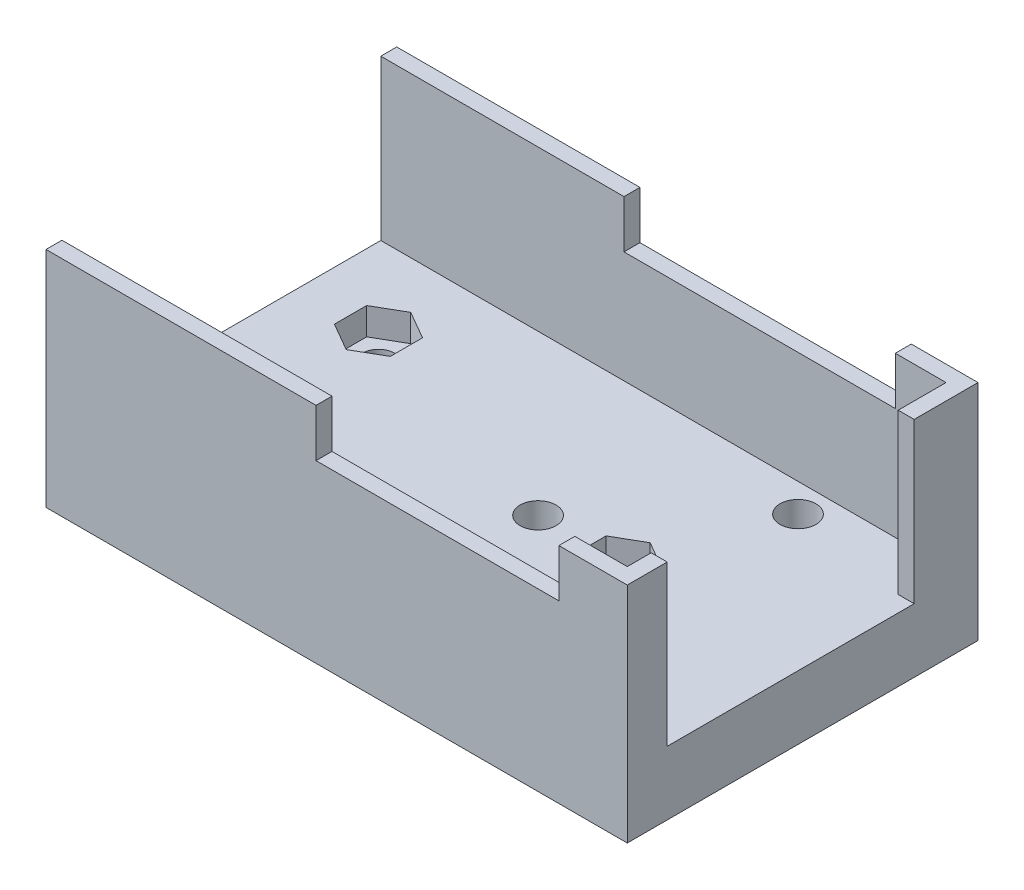
SolidWorks part; units mm, degrees
ref_plane "Front Plane" through (0, 0, 0) normal (0, 0, 1) x (1, 0, 0)
ref_plane "Top Plane" through (0, 0, 0) normal (0, 1, 0) x (1, 0, 0)
ref_plane "Right Plane" through (0, 0, 0) normal (1, 0, 0) x (0, 0, -1)
sketch "Sketch1" plane through (0, 0, 0) normal (0, 1, 0) x (1, 0, 0)
  line L0 (0, 2.5) -> (0, -2.5) construction
  line L1 (-33.5, 19.475) -> (33.5, 19.475) construction
  line L2 (-33.5, 19.475) -> (-33.5, -19.475) construction
  line L3 (-33.5, -19.475) -> (33.5, -19.475) construction
  line L4 (33.5, 19.475) -> (33.5, -19.475) construction
  line L5 (-2.5, 0) -> (2.5, 0) construction
  line L6 (-12.5, 19.475) -> (-12.5, -19.475) construction
  line L7 (30.5, 14.5022) -> (30.5, 19.3378) construction
  line L8 (23.7367, 16.92) -> (37.2633, 16.92) construction
  line L9 (30.5, -14.5022) -> (30.5, -19.3378) construction
  line L10 (23.7367, -16.92) -> (37.2633, -16.92) construction
  line L11 (30.5, 15.49) -> (29.1342, 15.49) construction
  line L12 (29.2815, -18.37) -> (31.7185, -18.37) construction
  line L13 (29.05, 15.9788) -> (29.05, 17.8612) construction
  line L14 (-10.95, -19.6462) -> (-10.95, -14.1938) construction
  line L15 (30.5, 15.47) -> (32.3745, 15.47) construction
  line L16 (30.5, -15.47) -> (32.3745, -15.47) construction
  line L17 (30.5, 15.47) -> (26.9196, 15.47) construction
  line L18 (30.5, 18.37) -> (26.9852, 18.37) construction
  line L19 (-12.5, 26.9594) -> (33.5, 26.9594) construction
  line L20 (10.5, 26.9594) -> (10.5, 19.475) construction
  line L21 (-9.5, 18.37) -> (-5.9852, 18.37) construction
  line L22 (-9.5, 15.47) -> (-5.9196, 15.47) construction
  line L23 (-9.5, -15.47) -> (-11.3745, -15.47) construction
  line L24 (-9.5, 15.47) -> (-11.3745, 15.47) construction
  line L25 (31.95, -19.2534) -> (31.95, -14.5866) construction
  line L26 (-8.7825, 18.36) -> (-7.3409, 18.36) construction
  line L28 (-9.5, 15.49) -> (-8.1342, 15.49) construction
  line L29 (-2.7367, -16.92) -> (-16.2633, -16.92) construction
  line L30 (-9.5, -14.5022) -> (-9.5, -19.3378) construction
  line L31 (-2.7367, 16.92) -> (-16.2633, 16.92) construction
  line L32 (-9.5, 14.5022) -> (-9.5, 19.3378) construction
  line L33 (-8.05, 16.2789) -> (-8.05, 17.5611) construction
  line L34 (-10.95, 15.8763) -> (-10.95, 17.9637) construction
  line L35 (31.95, 15.697) -> (31.95, 18.143) construction
  circle A4 centre (30.5, 16.92) radius 1.45 construction
  circle A5 centre (30.5, -16.92) radius 1.45 construction
  circle A6 centre (-9.5, -16.92) radius 1.45 construction
  circle A7 centre (-9.5, 16.92) radius 1.45 construction
  point P4 (0, 19.475)
  point P11 (0, 0)
  point P15 (0, 0)
  point P16 (-33.5, 0)
  point P22 (30.5, 16.92)
  point P24 (30.5, 16.92)
  point P32 (30.5, -18.37)
  point P35 (29.05, 16.92)
  point P56 (-10.95, -16.92)
  point P66 (31.95, -16.92)
  point P82 (-9.5, 16.92)
  point P83 (-9.5, 16.92)
  point P87 (-8.05, 16.92)
  point P89 (-10.95, 16.92)
  point P92 (31.95, 16.92)
  dimension "D7" = 30.94
  dimension "D9" = 42.9
  dimension "D1" = 5
  dimension "D2" = 5
  dimension "D3" = 38.95
  dimension "D4" = 67
  dimension "D5" = 46
  dimension "D6" = 21
  dimension "D8" = 36.74
  dimension "D10" = 1.105
  dimension "D11" = 0.02
  dimension "D12" = 0.02
  dimension "D13" = 0
  dimension "D14" = 1.55
  dimension "D15" = 37.1
  dimension "D16" = 42.9
sketch "Sketch2" plane through (0, 0, 0) normal (0, 1, 0) x (1, 0, 0)
  line L0 (-12.5, 19.475) -> (-12.5, -19.475) construction
  line L1 (-33.5, 19.475) -> (33.5, 19.475) construction
  line L2 (-33.5, 19.475) -> (-33.5, -19.475) construction
  line L3 (-33.5, -19.475) -> (33.5, -19.475) construction
  line L4 (33.5, 19.475) -> (33.5, -19.475) construction
  line L5 (17, 18.42) -> (21, 18.42) construction
  line L6 (-3, -14.475) -> (27.43, -14.475) construction
  line L7 (-3, -14.475) -> (-3, -19.475) construction
  line L9 (27.43, -14.475) -> (27.43, -19.475) construction
  line L11 (27.64, 19.475) -> (27.64, 14.475) construction
  line L12 (27.64, 14.475) -> (-6.36, 14.475) construction
  line L13 (-6.36, 19.475) -> (-6.36, 14.475) construction
  line L14 (0.85, 2) -> (4.85, 2) construction
  line L15 (0.85, 2) -> (0.85, -2) construction
  line L16 (0.85, -2) -> (4.85, -2) construction
  line L17 (4.85, 2) -> (4.85, -2) construction
  line L18 (17, 18.42) -> (17, 14.42) construction
  line L19 (17, 14.42) -> (21, 14.42) construction
  line L20 (21, 18.42) -> (21, 14.42) construction
  line L21 (17, -14.42) -> (21, -14.42) construction
  line L22 (17, -14.42) -> (17, -18.42) construction
  line L23 (17, -18.42) -> (21, -18.42) construction
  line L24 (21, -14.42) -> (21, -18.42) construction
  line L25 (19, 16.42) -> (19, -16.42) construction
  line L26 (19, 0) -> (11.327, 0) construction
  line L27 (30.5, -16.92) -> (24.299, -16.92) construction
  line L28 (29.05, -18.37) -> (31.95, -18.37)
  line L29 (29.05, -18.37) -> (29.05, -15.47)
  line L30 (29.05, -15.47) -> (31.95, -15.47)
  line L31 (31.95, -18.37) -> (31.95, -15.47)
  line L32 (29.05, -18.37) -> (31.95, -15.47) construction
  line L33 (29.05, -15.47) -> (31.95, -18.37) construction
  line L35 (-10.95, 15.47) -> (-8.05, 15.47)
  line L36 (-10.95, 15.47) -> (-10.95, 18.37)
  line L37 (-10.95, 18.37) -> (-8.05, 18.37)
  line L38 (-8.05, 15.47) -> (-8.05, 18.37)
  line L39 (-10.95, 15.47) -> (-8.05, 18.37) construction
  line L40 (-10.95, 18.37) -> (-8.05, 15.47) construction
  circle A0 centre (-9.5, 16.92) radius 1.45 construction
  circle A1 centre (30.5, 16.92) radius 1.45 construction
  circle A2 centre (30.5, -16.92) radius 1.45 construction
  circle A3 centre (-9.5, -16.92) radius 1.45 construction
  circle A4 centre (2.85, 0) radius 2 construction
  circle A7 centre (19, 16.42) radius 2 construction
  circle A8 centre (19, -16.42) radius 2 construction
  dimension "D8" = 4
  dimension "D9" = 4
  dimension "D10" = 4
  dimension "D1" = 9.5
  dimension "D2" = 30.43
  dimension "D3" = 6.07
  dimension "D4" = 5
  dimension "D5" = 34
  dimension "D6" = 5
  dimension "D7" = 6.14
  dimension "D11" = 36.84
  dimension "D12" = 20.15
  dimension "D13" = 14.95
  dimension "D14" = 31.95
  dimension "D15" = 42.9
  dimension "D16" = 36.84
sketch "Sketch3" plane through (0, 0, 0) normal (0, 1, 0) x (1, 0, 0)
  line L0 (-12.5, 19.975) -> (34, 19.975) construction
  line L1 (34, 19.975) -> (34, -19.975) construction
  line L2 (34, -19.975) -> (-12.5, -19.975) construction
  line L3 (-12.5, 19.975) -> (-36.8371, 19.975) construction
  line L4 (-12.5, -19.975) -> (-36.8371, -19.975) construction
  line L5 (-29.1596, 2.0082) -> (-25.1596, 2.0082) construction
  line L6 (33.5, 19.475) -> (33.5, -19.475) construction
  line L7 (-33.5, -19.475) -> (33.5, -19.475) construction
  line L8 (-36.8371, 19.975) -> (-36.8371, 21.975) construction
  line L9 (-36.8371, 21.975) -> (36, 21.975) construction
  line L11 (36, -21.975) -> (-36.8371, -21.975) construction
  line L12 (-36.8371, -21.975) -> (-36.8371, -19.975) construction
  line L13 (-29.1596, 12.0082) -> (-25.1596, 12.0082) construction
  line L14 (-29.1596, 12.0082) -> (-29.1596, 8.0082) construction
  line L15 (-29.1596, 8.0082) -> (-25.1596, 8.0082) construction
  line L16 (-25.1596, 12.0082) -> (-25.1596, 8.0082) construction
  line L17 (10.8404, 12.0082) -> (14.8404, 12.0082) construction
  line L18 (10.8404, 12.0082) -> (10.8404, 8.0082) construction
  line L19 (10.8404, 8.0082) -> (14.8404, 8.0082) construction
  line L20 (14.8404, 12.0082) -> (14.8404, 8.0082) construction
  line L21 (-29.1596, 2.0082) -> (-29.1596, -1.9918) construction
  line L22 (-29.1596, -1.9918) -> (-25.1596, -1.9918) construction
  line L23 (-25.1596, 2.0082) -> (-25.1596, -1.9918) construction
  line L24 (10.8404, 2.0082) -> (14.8404, 2.0082) construction
  line L25 (10.8404, 2.0082) -> (10.8404, -1.9918) construction
  line L26 (10.8404, -1.9918) -> (14.8404, -1.9918) construction
  line L27 (14.8404, 2.0082) -> (14.8404, -1.9918) construction
  line L28 (-19.1596, 2.0082) -> (-15.1596, 2.0082) construction
  line L29 (36, 21.975) -> (36, 13.975) construction
  line L30 (36, -21.975) -> (36, -16.975) construction
  line L31 (-19.1596, 12.0082) -> (-15.1596, 12.0082) construction
  line L32 (-19.1596, 12.0082) -> (-19.1596, 8.0082) construction
  line L33 (-19.1596, 8.0082) -> (-15.1596, 8.0082) construction
  line L34 (-15.1596, 12.0082) -> (-15.1596, 8.0082) construction
  line L35 (-9.1596, 12.0082) -> (-5.1596, 12.0082) construction
  line L36 (-9.1596, 12.0082) -> (-9.1596, 8.0082) construction
  line L37 (-9.1596, 8.0082) -> (-5.1596, 8.0082) construction
  line L38 (-5.1596, 12.0082) -> (-5.1596, 8.0082) construction
  line L39 (0.8404, 12.0082) -> (4.8404, 12.0082) construction
  line L40 (0.8404, 12.0082) -> (0.8404, 8.0082) construction
  line L41 (0.8404, 8.0082) -> (4.8404, 8.0082) construction
  line L42 (4.8404, 12.0082) -> (4.8404, 8.0082) construction
  line L43 (-19.1596, 2.0082) -> (-19.1596, -1.9918) construction
  line L44 (-19.1596, -1.9918) -> (-15.1596, -1.9918) construction
  line L45 (-15.1596, 2.0082) -> (-15.1596, -1.9918) construction
  line L46 (-9.1596, 2.0082) -> (-5.1596, 2.0082) construction
  line L47 (-9.1596, 2.0082) -> (-9.1596, -1.9918) construction
  line L48 (-9.1596, -1.9918) -> (-5.1596, -1.9918) construction
  line L49 (-5.1596, 2.0082) -> (-5.1596, -1.9918) construction
  line L50 (0.8404, 2.0082) -> (4.8404, 2.0082) construction
  line L51 (0.8404, 2.0082) -> (0.8404, -1.9918) construction
  line L52 (0.8404, -1.9918) -> (4.8404, -1.9918) construction
  line L53 (4.8404, 2.0082) -> (4.8404, -1.9918) construction
  line L54 (-29.1596, -7.9918) -> (-25.1596, -7.9918) construction
  line L55 (-29.1596, -7.9918) -> (-29.1596, -11.9918) construction
  line L56 (-29.1596, -11.9918) -> (-25.1596, -11.9918) construction
  line L57 (-25.1596, -7.9918) -> (-25.1596, -11.9918) construction
  line L58 (10.8404, -7.9918) -> (14.8404, -7.9918) construction
  line L59 (10.8404, -7.9918) -> (10.8404, -11.9918) construction
  line L60 (10.8404, -11.9918) -> (14.8404, -11.9918) construction
  line L61 (14.8404, -7.9918) -> (14.8404, -11.9918) construction
  line L62 (-19.1596, -7.9918) -> (-15.1596, -7.9918) construction
  line L63 (-19.1596, -7.9918) -> (-19.1596, -11.9918) construction
  line L64 (-19.1596, -11.9918) -> (-15.1596, -11.9918) construction
  line L65 (-15.1596, -7.9918) -> (-15.1596, -11.9918) construction
  line L66 (-9.1596, -7.9918) -> (-5.1596, -7.9918) construction
  line L67 (-9.1596, -7.9918) -> (-9.1596, -11.9918) construction
  line L68 (-9.1596, -11.9918) -> (-5.1596, -11.9918) construction
  line L69 (-5.1596, -7.9918) -> (-5.1596, -11.9918) construction
  line L70 (0.8404, -7.9918) -> (4.8404, -7.9918) construction
  line L71 (0.8404, -7.9918) -> (0.8404, -11.9918) construction
  line L72 (0.8404, -11.9918) -> (4.8404, -11.9918) construction
  line L73 (4.8404, -7.9918) -> (4.8404, -11.9918) construction
  circle A0 centre (-27.1596, 10.0082) radius 2 construction
  circle A1 centre (12.8404, 10.0082) radius 2 construction
  circle A4 centre (-17.1596, 10.0082) radius 2 construction
  circle A5 centre (-7.1596, 10.0082) radius 2 construction
  circle A6 centre (2.8404, 10.0082) radius 2 construction
  circle A7 centre (-27.1596, 0.0082) radius 2 construction
  circle A8 centre (12.8404, 0.0082) radius 2 construction
  circle A9 centre (-17.1596, 0.0082) radius 2 construction
  circle A10 centre (-7.1596, 0.0082) radius 2 construction
  circle A11 centre (2.8404, 0.0082) radius 2 construction
  circle A12 centre (-27.1596, -9.9918) radius 2 construction
  circle A13 centre (12.8404, -9.9918) radius 2 construction
  circle A14 centre (-17.1596, -9.9918) radius 2 construction
  circle A15 centre (-7.1596, -9.9918) radius 2 construction
  circle A16 centre (2.8404, -9.9918) radius 2 construction
  point P6 (-4.9675, 10.0082)
  point P107 (-7.1596, 10.0082)
  dimension "D7" = 4
  dimension "D8" = 4
  dimension "D9" = 10
  dimension "D10" = 72.8371
  dimension "D2" = 0.5
  dimension "D3" = 0.5
  dimension "D4" = 2
  dimension "D5" = 5
  dimension "D6" = 2
  dimension "D11" = 46.5
  dimension "D12" = 39.95
  dimension "D13" = 3
  dimension "D14" = 4
  dimension "8" = 8
  dimension "D17" = 2
  dimension "D19" = 10
  dimension "D20" = 2
sketch "Sketch4" plane through (0, 0, 0) normal (0, 1, 0) x (1, 0, 0)
  line L1 (-36.8371, 21.975) -> (36, 21.975)
  line L2 (-36.8371, 21.975) -> (-36.8371, -21.975)
  line L3 (-36.8371, -21.975) -> (36, -21.975)
  line L4 (36, 21.975) -> (36, -21.975)
extrude "Boss-Extrude1" add sketch "Sketch4" along normal blind 8 contours L2 L3 L4 L1
sketch "Sketch5" plane through (0, 8, 0) normal (0, 1, 0) x (1, 0, 0)
  line L0 (36, 13.975) -> (34, 13.975)
  line L1 (-36.8371, 21.975) -> (36, 21.975)
  line L3 (-36.8371, -21.975) -> (36, -21.975)
  line L4 (36, 21.975) -> (36, 13.975)
  line L5 (34, 19.975) -> (-36.8371, 19.975)
  line L6 (34, 19.975) -> (34, 13.975)
  line L7 (34, -19.975) -> (-36.8371, -19.975)
  line L9 (36, -16.975) -> (34, -16.975)
  line L10 (-36.8371, 21.975) -> (-36.8371, 19.975)
  line L11 (-36.8371, -19.975) -> (-36.8371, -21.975)
  line L12 (34, -16.975) -> (34, -19.975)
  line L13 (36, -16.975) -> (36, -21.975)
extrude "Boss-Extrude2" add sketch "Sketch5" along normal blind 14
sketch "Sketch6" plane through (0, 22, 0) normal (0, 1, 0) x (1, 0, 0)
  line L0 (-12.5, 19.975) -> (34, 19.975) construction
  line L1 (-36.8371, 21.975) -> (-6.36, 21.975)
  line L2 (-36.8371, 21.975) -> (-36.8371, 19.975)
  line L3 (-36.8371, 19.975) -> (-6.36, 19.975)
  line L4 (-6.36, 21.975) -> (-6.36, 19.975)
  line L5 (-6.36, 19.475) -> (-6.36, 14.475) construction
  line L6 (36, 21.975) -> (27.64, 21.975)
  line L7 (36, 21.975) -> (36, 13.975)
  line L8 (36, 13.975) -> (34, 13.975)
  line L9 (27.64, 21.975) -> (27.64, 19.975)
  line L10 (34, 19.975) -> (27.64, 19.975)
  line L11 (34, 19.975) -> (34, 13.975)
  line L14 (36, -21.975) -> (27.43, -21.975)
  line L15 (36, -21.975) -> (36, -16.975)
  line L16 (36, -16.975) -> (34, -16.975)
  line L17 (27.43, -21.975) -> (27.43, -19.975)
  line L18 (-3, -14.475) -> (-3, -19.475) construction
  line L19 (36, -16.975) -> (34, -16.975) construction
  line L20 (34, -19.975) -> (27.43, -19.975)
  line L21 (34, -19.975) -> (34, -16.975)
  line L24 (27.43, -14.475) -> (27.43, -19.475) construction
  line L25 (36, -21.975) -> (-36.8371, -21.975) construction
  line L26 (-36.8371, -19.975) -> (-3, -19.975)
  line L27 (-36.8371, -19.975) -> (-36.8371, -21.975)
  line L28 (-36.8371, -21.975) -> (-3, -21.975)
  line L29 (-3, -19.975) -> (-3, -21.975)
  dimension "D1" = 34
extrude "Boss-Extrude3" add sketch "Sketch6" along normal blind 6
hole_wizard "CBORE for M4 SHCS1" positions "Sketch7" profile "Sketch8" counterbore size "M4" standard "ANSI Metric" end condition through all
sketch "Sketch7" plane through (0, 0, 0) normal (0, -1, 0) x (-1, 0, 0)
  point P0 (-2.85, 0)
  point P3 (-19, 16.42)
  point P6 (-19, -16.42)
sketch "Sketch8" plane through (2.85, 0, 0) normal (1, 0, 0) x (0, 0, -1)
  line L0 (0, 0) -> (0, 28)
  line L1 (0, 28) -> (2.25, 28)
  line L3 (2.25, 28) -> (2.25, 4)
  line L4 (2.25, 4) -> (4, 4)
  line L5 (4, 4) -> (4, 0)
  line L7 (4, 0) -> (0, 0)
  line L11 (0, -6.35) -> (0, 107.95) construction
  dimension "Thru Hole Dia." = 4.5
  dimension "Thru Hole Depth" = 28
  dimension "C'Bore Dia." = 8
  dimension "C'Bore Depth" = 4
sketch "Sketch9" plane through (0, 0, 21.975) normal (0, 0, 1) x (1, 0, 0)
  line L0 (-36.8371, 0) -> (36, 0) construction
  line L1 (-16.7068, 0) -> (31.3494, 0)
  line L2 (-16.7068, 0) -> (-16.7068, 2.7374)
  line L3 (-16.7068, 2.7374) -> (31.3494, 2.7374)
  line L4 (31.3494, 0) -> (31.3494, 2.7374)
hole_wizard "Ø4.0mm Dowel Hole1" positions "Sketch10" profile "Sketch11" hole size "Ø4.0" standard "ANSI Metric" end condition through all
sketch "Sketch10" plane through (0, 0, 0) normal (0, -1, 0) x (-1, 0, 0)
  point P0 (-12.8404, 0.0082)
  point P3 (27.1596, 10.0082)
  point P6 (27.1596, -9.9918)
sketch "Sketch11" plane through (12.8404, 0, -0.0082) normal (1, 0, 0) x (0, 0, -1)
  line L0 (0, 0) -> (0, 28)
  line L1 (0, 28) -> (2, 28)
  line L2 (2, 28) -> (2, 0)
  line L5 (2, 0) -> (0, 0)
  line L11 (0, -6.35) -> (0, 107.95) construction
  dimension "Thru Hole Dia." = 4
  dimension "Thru Hole Depth" = 28
sketch "Sketch12" plane through (0, 8, 0) normal (0, 1, 0) x (1, 0, 0)
  line L1 (12.8404, 4.0496) -> (9.3404, 2.0289)
  line L2 (9.3404, 2.0289) -> (9.3404, -2.0126)
  line L3 (9.3404, -2.0126) -> (12.8404, -4.0333)
  line L4 (12.8404, -4.0333) -> (16.3404, -2.0126)
  line L5 (16.3404, -2.0126) -> (16.3404, 2.0289)
  line L6 (16.3404, 2.0289) -> (12.8404, 4.0496)
  line L7 (-27.1596, 14.0496) -> (-30.6596, 12.0289)
  line L8 (-30.6596, 12.0289) -> (-30.6596, 7.9874)
  line L9 (-30.6596, 7.9874) -> (-27.1596, 5.9667)
  line L10 (-27.1596, 5.9667) -> (-23.6596, 7.9874)
  line L11 (-23.6596, 7.9874) -> (-23.6596, 12.0289)
  line L12 (-23.6596, 12.0289) -> (-27.1596, 14.0496)
  line L13 (-27.1596, -5.9504) -> (-30.6596, -7.9711)
  line L14 (-30.6596, -7.9711) -> (-30.6596, -12.0126)
  line L15 (-30.6596, -12.0126) -> (-27.1596, -14.0333)
  line L16 (-27.1596, -14.0333) -> (-23.6596, -12.0126)
  line L17 (-23.6596, -12.0126) -> (-23.6596, -7.9711)
  line L18 (-23.6596, -7.9711) -> (-27.1596, -5.9504)
  circle A0 centre (12.8404, 0.0082) radius 3.5 construction
  circle A1 centre (-27.1596, 10.0082) radius 3.5 construction
  circle A2 centre (-27.1596, -9.9918) radius 3.5 construction
  dimension "D1" = 7
  dimension "D2" = 7
  dimension "D3" = 7
extrude "Cut-Extrude1" cut sketch "Sketch12" against normal blind 3.4
